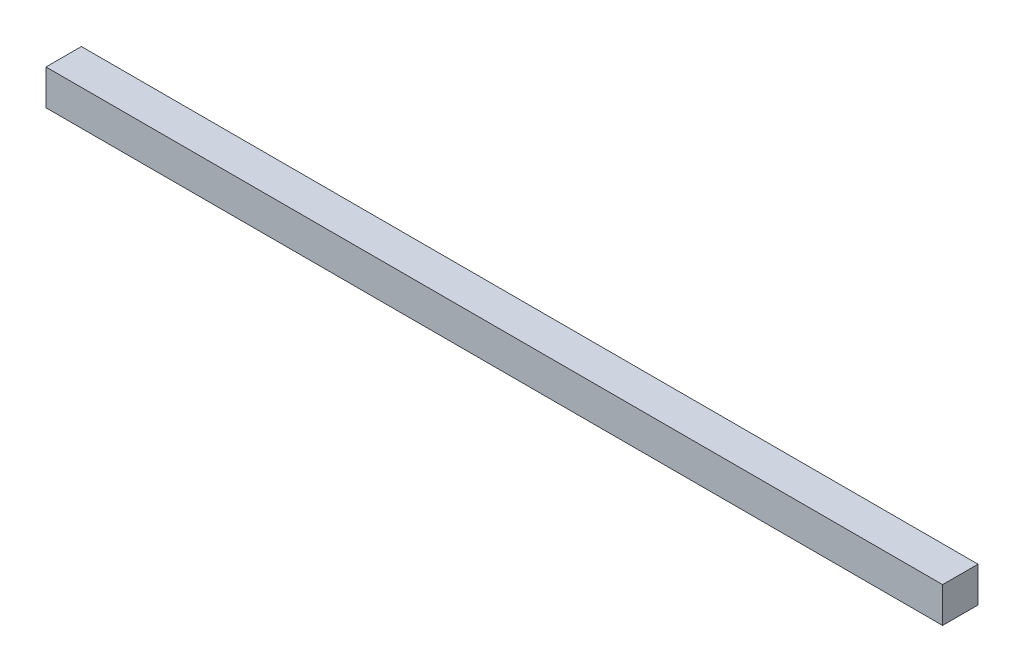
SolidWorks part; units mm, degrees
ref_plane "Front Plane" through (0, 0, 0) normal (0, 0, 1) x (1, 0, 0)
ref_plane "Top Plane" through (0, 0, 0) normal (0, 1, 0) x (1, 0, 0)
ref_plane "Right Plane" through (0, 0, 0) normal (1, 0, 0) x (0, 0, -1)
sketch "Sketch1" plane through (0, 0, 0) normal (0, 1, 0) x (1, 0, 0)
  line L1 (38, -1.5) -> (-38, -1.5)
  line L2 (38, -1.5) -> (38, 1.5)
  line L3 (38, 1.5) -> (-38, 1.5)
  line L4 (-38, -1.5) -> (-38, 1.5)
  line L5 (38, -1.5) -> (-38, 1.5) construction
  line L6 (38, 1.5) -> (-38, -1.5) construction
  point P0 (0, 0)
  dimension "D1" = 3
  dimension "D2" = 76
extrude "Boss-Extrude1" add sketch "Sketch1" along normal mid plane 3
